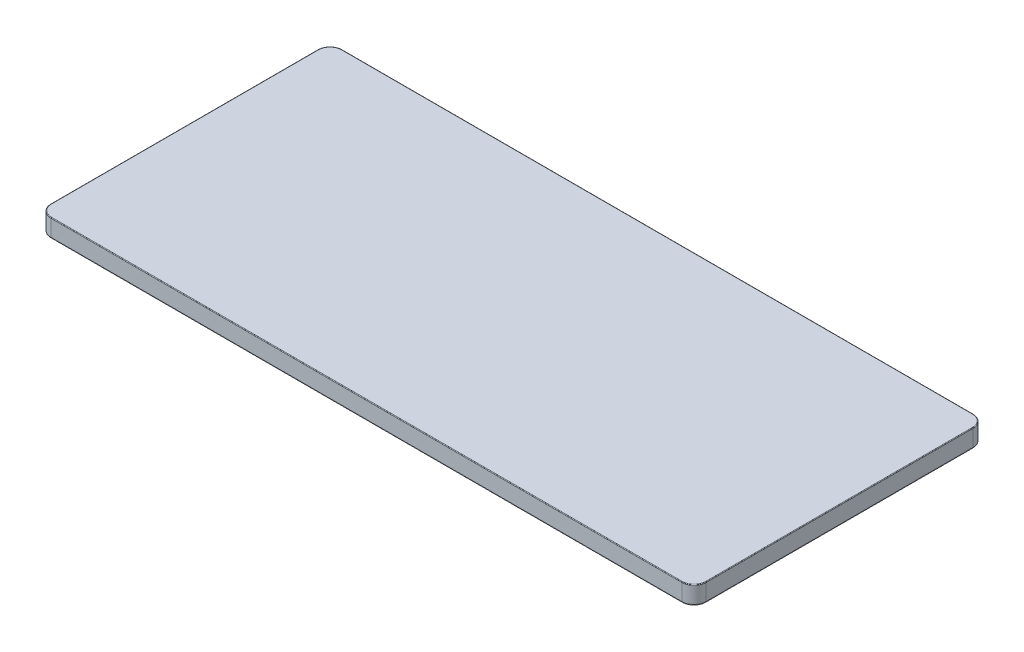
SolidWorks part; units mm, degrees
ref_plane "Front Plane" through (0, 0, 0) normal (0, 0, 1) x (1, 0, 0)
ref_plane "Top Plane" through (0, 0, 0) normal (0, 1, 0) x (1, 0, 0)
ref_plane "Right Plane" through (0, 0, 0) normal (1, 0, 0) x (0, 0, -1)
sketch "Sketch1" plane through (0, 0, 0) normal (0, 1, 0) x (1, 0, 0)
  line L1 (-660.4, -304.8) -> (660.4, -304.8)
  line L2 (-685.8, -279.4) -> (-685.8, 279.4)
  line L3 (-660.4, 304.8) -> (660.4, 304.8)
  line L4 (685.8, -279.4) -> (685.8, 279.4)
  line L5 (-685.8, -304.8) -> (685.8, 304.8) construction
  line L6 (-685.8, 304.8) -> (685.8, -304.8) construction
  arc A0 (660.4, -304.8) -> (685.8, -279.4) centre (660.4, -279.4) ccw
  arc A1 (660.4, 304.8) -> (685.8, 279.4) centre (660.4, 279.4) cw
  arc A2 (-685.8, 279.4) -> (-660.4, 304.8) centre (-660.4, 279.4) cw
  arc A3 (-660.4, -304.8) -> (-685.8, -279.4) centre (-660.4, -279.4) cw
  point P0 (0, 0)
  dimension "D3" = 25.4
  dimension "D1" = 1371.6
  dimension "D2" = 609.6
extrude "Boss-Extrude1" add sketch "Sketch1" against normal blind 38.1
fillet "Fillet1" radius 2.54 8 edges at (-678.3605, -38.1, 297.3605) (-685.8, -38.1, 0) (-678.3605, -38.1, -297.3605) (0, -38.1, -304.8) (678.3605, -38.1, -297.3605) (685.8, -38.1, 0) (678.3605, -38.1, 297.3605) (0, -38.1, 304.8)
fillet "Fillet2" radius 1.27 8 edges at (-678.3605, 0, 297.3605) (-685.8, 0, 0) (-678.3605, 0, -297.3605) (0, 0, -304.8) (678.3605, 0, -297.3605) (685.8, 0, 0) (678.3605, 0, 297.3605) (0, 0, 304.8)
sketch "Sketch2" plane through (0, -38.1, 0) normal (0, -1, 0) x (1, 0, 0)
  line L0 (0, -302.26) -> (0, 302.26) construction
  line L1 (660.4, 302.26) -> (-660.4, 302.26) construction
  line L2 (-683.26, 0) -> (683.26, 0) construction
  line L3 (683.26, -279.4) -> (683.26, 279.4) construction
  circle A0 centre (-457.2, 127) radius 1.5875
  circle A1 centre (-342.9, 127) radius 1.5875
  circle A2 centre (342.9, 127) radius 1.5875
  circle A3 centre (457.2, 127) radius 1.5875
  circle A4 centre (-342.9, -127) radius 1.5875
  circle A5 centre (-457.2, -127) radius 1.5875
  circle A6 centre (457.2, -127) radius 1.5875
  circle A7 centre (342.9, -127) radius 1.5875
  point P6 (0, 0)
  point P12 (0, 0)
  dimension "D1" = 3.175
  dimension "D2" = 114.3
  dimension "D3" = 127
  dimension "D4" = 914.4
extrude "Cut-Extrude1" cut sketch "Sketch2" against normal blind 12.7 contours A0 | A1 | A5 | A4 | A2 | A3 | A7 | A6
